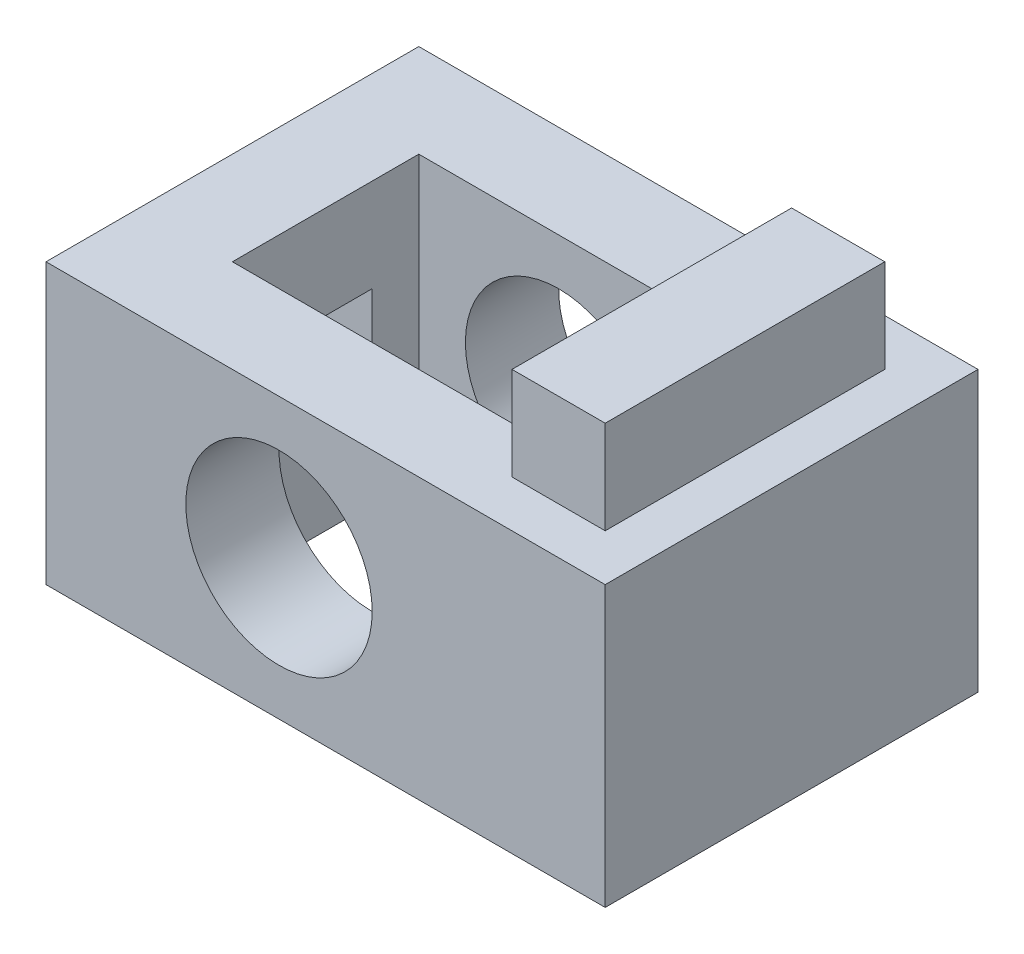
SolidWorks part; units mm, degrees
ref_plane "Front Plane" through (0, 0, 0) normal (0, 0, 1) x (1, 0, 0)
ref_plane "Top Plane" through (0, 0, 0) normal (0, 1, 0) x (1, 0, 0)
ref_plane "Right Plane" through (0, 0, 0) normal (1, 0, 0) x (0, 0, -1)
sketch "Sketch2" plane through (0, 0, 0) normal (1, 0, 0) x (0, 0, -1)
  line L1 (-101.6, 76.2) -> (101.6, 76.2)
  line L2 (-101.6, 76.2) -> (-101.6, -76.2)
  line L3 (-101.6, -76.2) -> (101.6, -76.2)
  line L4 (101.6, 76.2) -> (101.6, -76.2)
  point P4 (0, 76.2)
  point P5 (101.6, 0)
  dimension "D1" = 152.4
  dimension "D2" = 203.2
extrude "Boss-Extrude1" add sketch "Sketch2" along normal mid plane 304.8
sketch "Sketch3" plane through (0, 76.2, 0) normal (0, 1, 0) x (1, 0, 0)
  line L1 (-101.6, 50.8) -> (50.8, 50.8)
  line L2 (-101.6, 50.8) -> (-101.6, -50.8)
  line L3 (-101.6, -50.8) -> (50.8, -50.8)
  line L4 (50.8, 50.8) -> (50.8, -50.8)
  line L5 (-152.4, 101.6) -> (-152.4, -101.6) construction
  point P5 (-101.6, 0)
  dimension "D1" = 101.6
  dimension "D2" = 152.4
  dimension "D3" = 50.8
sketch "Sketch5" plane through (0, 76.2, 0) normal (0, 1, 0) x (1, 0, 0)
  line L0 (152.4, 101.6) -> (152.4, -101.6) construction
  line L1 (76.2, 76.2) -> (127, 76.2)
  line L2 (76.2, 76.2) -> (76.2, -76.2)
  line L3 (76.2, -76.2) -> (127, -76.2)
  line L4 (127, 76.2) -> (127, -76.2)
  point P4 (76.2, 0)
  dimension "D1" = 152.4
  dimension "D2" = 50.8
  dimension "D3" = 25.4
sketch "Sketch6" plane through (0, 0, 101.6) normal (0, 0, 1) x (1, 0, 0)
  line L0 (-152.4, 76.2) -> (-152.4, -76.2) construction
  circle A0 centre (-25.4, 0) radius 50.8
  dimension "D1" = 101.6
  dimension "D2" = 127
extrude "Cut-Extrude2" cut sketch "Sketch6" against normal blind 228.6
sketch "Sketch7" plane through (-152.4, 0, 0) normal (-1, 0, 0) x (0, 0, 1)
  line L1 (-25.4, 25.4) -> (25.4, 25.4)
  line L2 (-25.4, 25.4) -> (-25.4, -25.4)
  line L3 (-25.4, -25.4) -> (25.4, -25.4)
  line L4 (25.4, 25.4) -> (25.4, -25.4)
  point P4 (-25.4, 0)
  point P5 (0, 25.4)
  dimension "D1" = 50.8
extrude "Cut-Extrude3" cut sketch "Sketch7" against normal blind 50.8
extrude "Boss-Extrude3" add sketch "Sketch5" along normal blind 50.8
extrude "Cut-Extrude4" cut sketch "Sketch3" against normal blind 228.6
